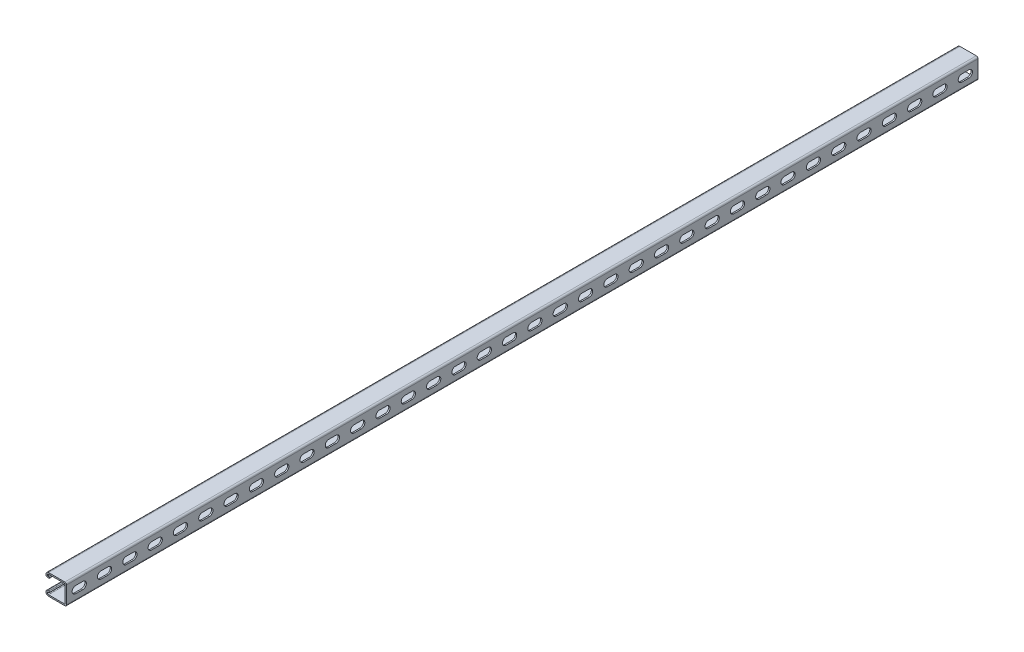
SolidWorks part; units mm, degrees
material "Galvanized Steel"
ref_plane "Front Plane" through (0, 0, 0) normal (0, 0, 1) x (1, 0, 0)
ref_plane "Top Plane" through (0, 0, 0) normal (0, 1, 0) x (1, 0, 0)
ref_plane "Right Plane" through (0, 0, 0) normal (1, 0, 0) x (0, 0, -1)
sketch "Sketch1" plane through (0, 0, 0) normal (0, 0, 1) x (1, 0, 0)
  line L0 (0, 0) -> (-41.275, 0) construction
  line L3 (-41.275, 20.6375) -> (0, 20.6375) construction
  line L4 (-41.275, 20.6375) -> (-41.275, -20.6375) construction
  line L5 (-41.275, -20.6375) -> (0, -20.6375) construction
  line L6 (0, 20.6375) -> (0, -20.6375) construction
  line L7 (-36.2267, 20.6375) -> (-3.4607, 20.6375)
  line L8 (0, 17.1767) -> (0, -17.1767)
  line L9 (-2.794, -17.1767) -> (-2.794, 17.1767)
  line L10 (-3.4608, 17.8435) -> (-36.2267, 17.8435)
  line L11 (-41.275, 15.5892) -> (-41.275, 14.5732)
  line L12 (-37.8142, 11.1125) -> (-35.5346, 11.1125)
  line L14 (-35.5346, 13.9065) -> (-37.8142, 13.9065)
  line L15 (-38.481, 14.5732) -> (-38.481, 15.5892)
  line L16 (-38.481, -14.5733) -> (-38.481, -15.5893)
  line L17 (-35.5346, -13.9065) -> (-37.8142, -13.9065)
  line L18 (-37.8142, -11.1125) -> (-35.5346, -11.1125)
  line L19 (-41.275, -15.5893) -> (-41.275, -14.5733)
  line L20 (-3.4607, -17.8435) -> (-36.2267, -17.8435)
  line L21 (-36.2267, -20.6375) -> (-3.4607, -20.6375)
  line L22 (-2.794, -20.6375) -> (-2.794, 20.6375) construction
  arc A1 (0, 17.1767) -> (-3.4607, 20.6375) centre (-3.4607, 17.1767) ccw
  arc A2 (-2.794, 17.1767) -> (-3.4608, 17.8435) centre (-3.4607, 17.1767) ccw
  arc A4 (-36.2267, 20.6375) -> (-41.275, 15.5892) centre (-36.2267, 15.5892) ccw
  arc A5 (-41.275, 14.5732) -> (-37.8142, 11.1125) centre (-37.8142, 14.5732) ccw
  arc A6 (-35.5346, 11.1125) -> (-35.5346, 13.9065) centre (-35.5346, 12.5095) ccw
  arc A7 (-37.8142, 13.9065) -> (-38.481, 14.5732) centre (-37.8142, 14.5732) cw
  arc A8 (-38.481, 15.5892) -> (-36.2267, 17.8435) centre (-36.2267, 15.5892) cw
  arc A9 (-38.481, -15.5893) -> (-36.2267, -17.8435) centre (-36.2267, -15.5893) ccw
  arc A10 (-37.8142, -13.9065) -> (-38.481, -14.5733) centre (-37.8142, -14.5733) ccw
  arc A11 (-35.5346, -11.1125) -> (-35.5346, -13.9065) centre (-35.5346, -12.5095) cw
  arc A12 (-41.275, -14.5733) -> (-37.8142, -11.1125) centre (-37.8142, -14.5733) cw
  arc A13 (-36.2267, -20.6375) -> (-41.275, -15.5893) centre (-36.2267, -15.5893) cw
  arc A14 (-2.794, -17.1767) -> (-3.4607, -17.8435) centre (-3.4607, -17.1767) cw
  arc A15 (0, -17.1767) -> (-3.4607, -20.6375) centre (-3.4607, -17.1767) cw
  point P24 (0, 20.6375)
  point P65 (-2.794, 0)
  dimension "D1" = 3.4608
  dimension "D2" = 5.0482
  dimension "D3" = 3.4608
  dimension "Ht." = 41.275
  dimension "Wd." = 41.275
  dimension "Thk." = 2.794
  dimension "D4" = 9.525
  dimension "D5" = 7.1374
extrude "Boss-Extrude1" add sketch "Sketch1" against normal blind 1828.8
sketch "Sketch3" plane through (0, 0, 0) normal (1, 0, 0) x (0, 0, -1)
  line L0 (0, 0) -> (1828.8, 0) construction
  point P2 (101.6, 0)
  point P3 (1727.2, 0)
  dimension "D1" = 101.6
  dimension "D2" = 101.6
  dimension "D3" = 1828.8
sketch "Sketch2" plane through (0, 0, 0) normal (1, 0, 0) x (0, 0, -1)
  line L0 (18.2562, 0) -> (32.5437, 0) construction
  line L1 (18.2562, 7.1437) -> (32.5437, 7.1437)
  line L2 (18.2562, -7.1437) -> (32.5437, -7.1437)
  line L3 (18.2562, 0) -> (0, 0) construction
  line L4 (25.4, 0) -> (76.2, 0) construction
  line L5 (0, -17.1767) -> (0, 17.1767) construction
  arc A0 (18.2562, 7.1437) -> (18.2562, -7.1437) centre (18.2562, 0) ccw
  arc A1 (32.5437, -7.1437) -> (32.5437, 7.1437) centre (32.5437, 0) ccw
  point P3 (25.4, 0)
  dimension "Hole to End" = 11.1125
  dimension "D2" = 25.4
extrude "Cut-Extrude1" cut sketch "Sketch2" against normal up to vertex (2.794 mm away) up to point (-2.794, 0, 0)
pattern_linear "LPattern1" count 36 spacing 50.8 along (0, 0, -1) of "Cut-Extrude1"
equation "\"D1@LPattern1\" = \"Slot Ctr.@Sketch2\""
equation "\"Hole Count@LPattern1\" = \"Lg.@Boss-Extrude1\" / \"D1@LPattern1\""
equation "\"D3@Sketch3\" = \"Lg.@Boss-Extrude1\""
